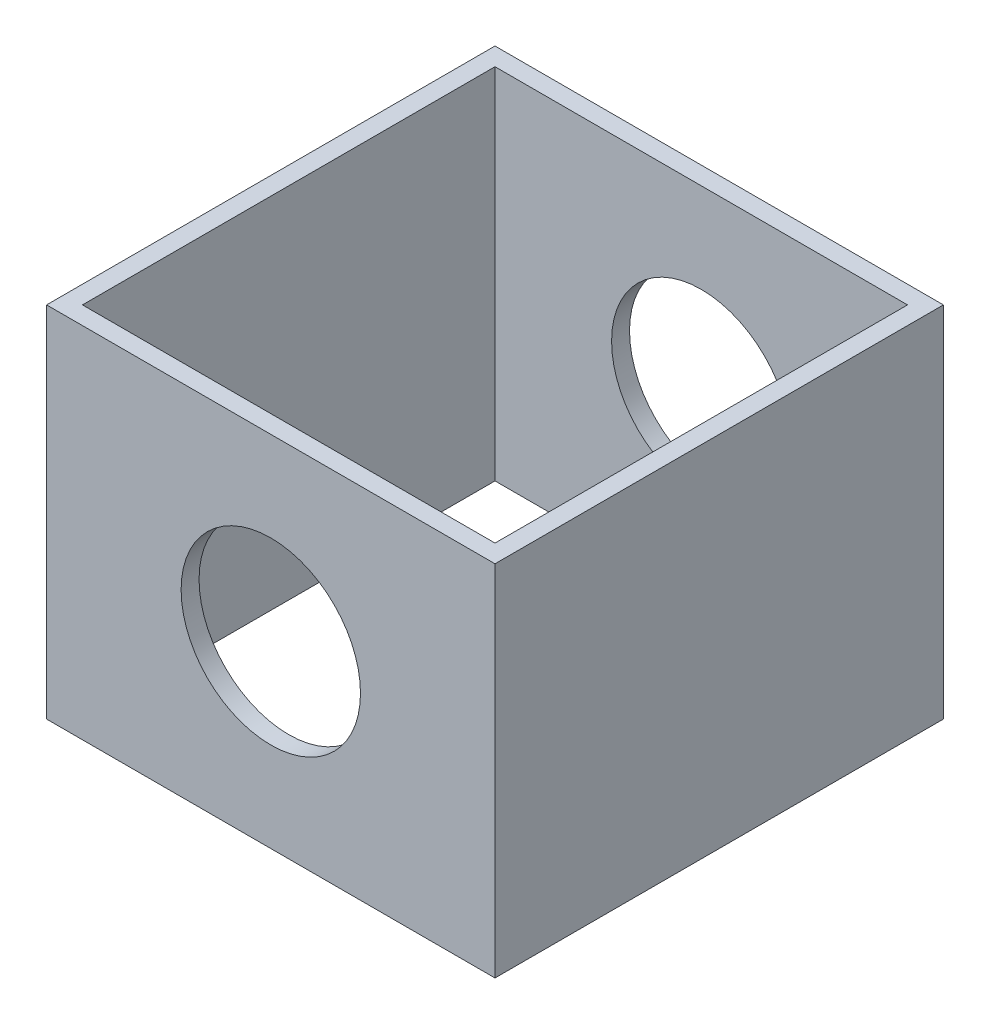
SolidWorks part; units mm, degrees
ref_plane "Front Plane" through (0, 0, 0) normal (0, 0, 1) x (1, 0, 0)
ref_plane "Top Plane" through (0, 0, 0) normal (0, 1, 0) x (1, 0, 0)
ref_plane "Right Plane" through (0, 0, 0) normal (1, 0, 0) x (0, 0, -1)
sketch "Sketch1" plane through (0, 0, 0) normal (0, 1, 0) x (1, 0, 0)
  line L0 (-30.48, -1.27) -> (-30.48, 30.48)
  line L1 (0, 0) -> (-29.21, 0)
  line L2 (0, 0) -> (0, 29.21)
  line L3 (0, 29.21) -> (-29.21, 29.21)
  line L4 (-29.21, 0) -> (-29.21, 29.21)
  line L5 (1.27, 30.48) -> (-30.48, 30.48)
  line L6 (1.27, -1.27) -> (1.27, 30.48)
  line L7 (1.27, -1.27) -> (-30.48, -1.27)
  dimension "D1" = 29.21
  dimension "D2" = 1.27
extrude "Boss-Extrude1" add sketch "Sketch1" along normal blind 25.4
sketch "Sketch2" plane through (0, 0, 1.27) normal (0, 0, 1) x (1, 0, 0)
  line L8 (1.27, 0) -> (-30.48, 25.4) construction
  circle A0 centre (-14.605, 12.7) radius 6.35
  dimension "D1" = 12.7
extrude "Cut-Extrude1" cut sketch "Sketch2" against normal up to surface (31.75 mm away) up to face at (-14.605, 12.7, -30.48)
